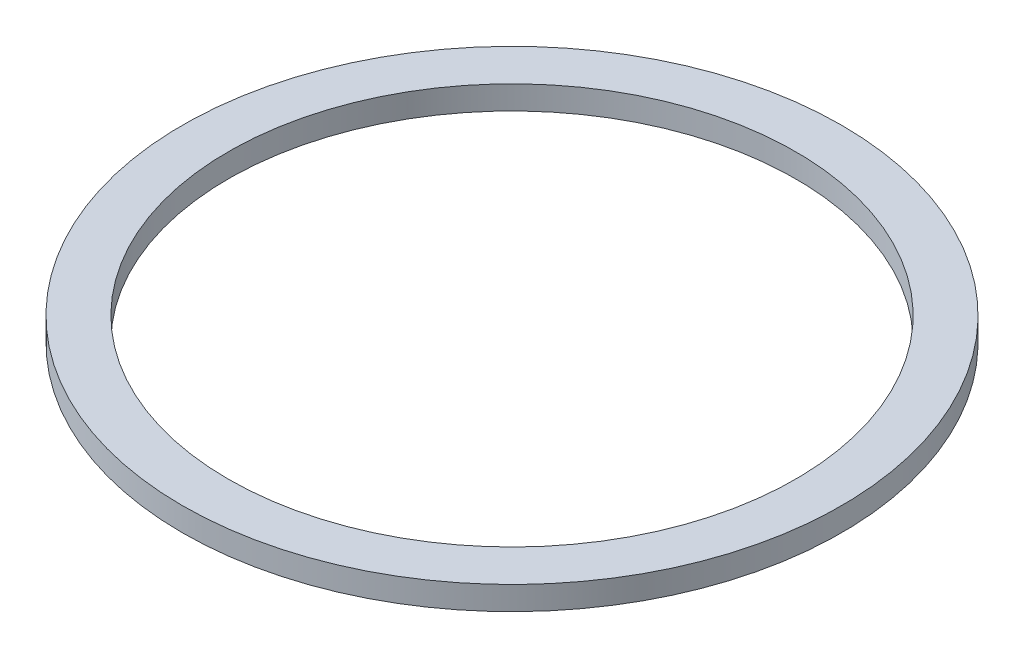
SolidWorks part; units mm, degrees
material "1023 Carbon Steel Sheet (SS)"
ref_plane "Front Plane" through (0, 0, 0) normal (0, 0, 1) x (1, 0, 0)
ref_plane "Top Plane" through (0, 0, 0) normal (0, 1, 0) x (1, 0, 0)
ref_plane "Right Plane" through (0, 0, 0) normal (1, 0, 0) x (0, 0, -1)
sketch "Sketch1" plane through (0, 0, 0) normal (0, 1, 0) x (1, 0, 0)
  circle A0 centre (0, 0) radius 14
  circle A1 centre (0, 0) radius 12.05
  dimension "D1" = 28
  dimension "D2" = 24.1
extrude "Boss-Extrude1" add sketch "Sketch1" along normal blind 1
